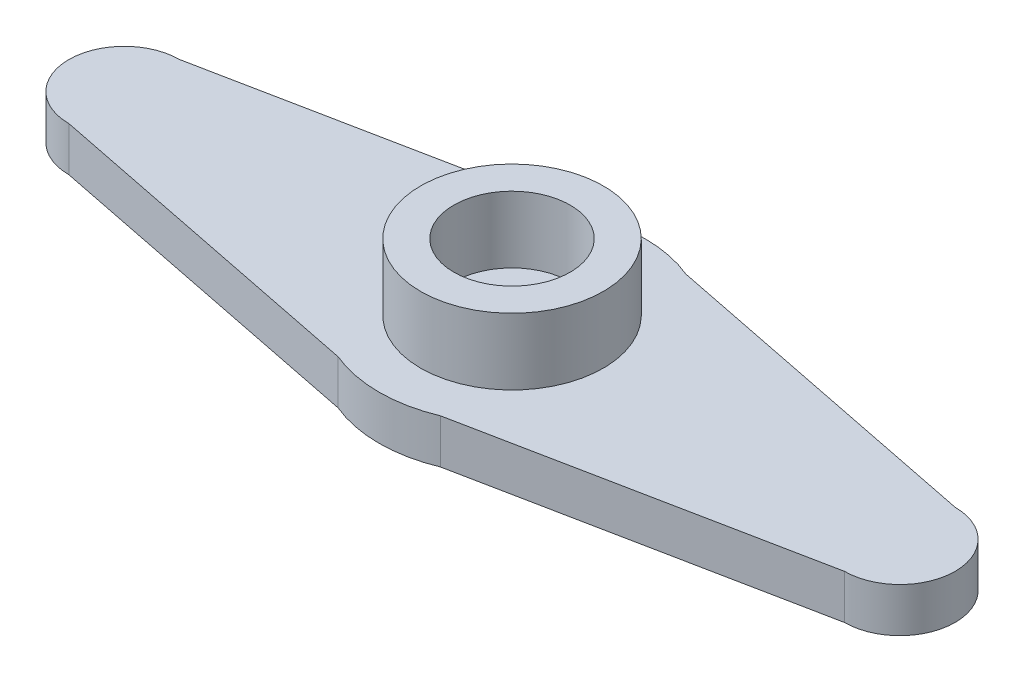
SolidWorks part; units mm, degrees
ref_plane "Front Plane" through (0, 0, 0) normal (0, 0, 1) x (1, 0, 0)
ref_plane "Top Plane" through (0, 0, 0) normal (0, 1, 0) x (1, 0, 0)
ref_plane "Right Plane" through (0, 0, 0) normal (1, 0, 0) x (0, 0, -1)
sketch "Sketch1" plane through (0, 0, 0) normal (0, 1, 0) x (1, 0, 0)
  line L0 (-26.1977, 0) -> (26.1977, 0) construction
  line L1 (17.5, 2.5) -> (2.3077, 5.5385)
  line L2 (-2.3077, 5.5385) -> (-17.5, 2.5)
  line L3 (17.5, -2.5) -> (2.3077, -5.5385)
  line L4 (-2.3077, -5.5385) -> (-17.5, -2.5)
  arc A0 (2.3077, 5.5385) -> (-2.3077, 5.5385) centre (0, 0) ccw
  arc A1 (-17.5, 2.5) -> (-17.5, -2.5) centre (-17.5, 0) ccw
  arc A2 (17.5, -2.5) -> (17.5, 2.5) centre (17.5, 0) ccw
  arc A3 (-2.3077, -5.5385) -> (2.3077, -5.5385) centre (0, 0) ccw
  dimension "D1" = 12
  dimension "D4" = 5
  dimension "D5" = 5
  dimension "D2" = 17.5
  dimension "D3" = 17.5
  dimension "D6" = 15.1923
  dimension "D7" = 15.1923
  dimension "D8" = 15.1923
  dimension "D9" = 15.1923
extrude "Boss-Extrude1" add sketch "Sketch1" along normal blind 2
sketch "Sketch2" plane through (0, 2, 0) normal (0, 1, 0) x (1, 0, 0)
  circle A0 centre (0, 0) radius 4.125
  circle A1 centre (0, 0) radius 2.625
  dimension "D1" = 8.25
  dimension "D2" = 5.25
extrude "Boss-Extrude2" add sketch "Sketch2" along normal blind 3
